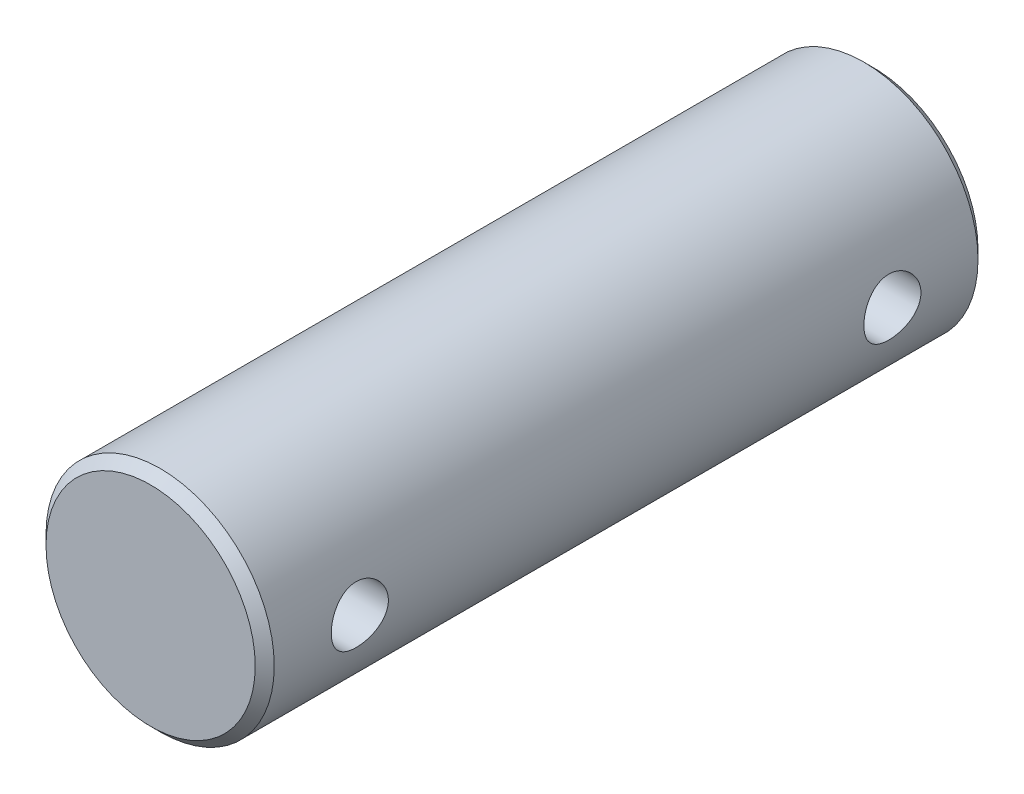
SolidWorks part; units mm, degrees
ref_plane "Front Plane" through (0, 0, 0) normal (0, 0, 1) x (1, 0, 0)
ref_plane "Top Plane" through (0, 0, 0) normal (0, 1, 0) x (1, 0, 0)
ref_plane "Right Plane" through (0, 0, 0) normal (1, 0, 0) x (0, 0, -1)
sketch "Sketch1" plane through (0, 0, 0) normal (0, 0, 1) x (1, 0, 0)
  circle A0 centre (0, 0) radius 6
  dimension "D1" = 12
extrude "Boss-Extrude1" add sketch "Sketch1" against normal blind 38
sketch "Sketch2" plane through (0, 0, 0) normal (1, 0, 0) x (0, 0, -1)
  line L0 (38, -6) -> (38, 6) construction
  circle A0 centre (5, 0) radius 1.5
  circle A1 centre (33, 0) radius 1.5
  dimension "D1" = 3
  dimension "D2" = 5
  dimension "D3" = 5
extrude "Cut-Extrude1" cut sketch "Sketch2" against normal through all both and the other way through all
chamfer "Chamfer1" distance 0.5 angle 45 2 edges at (6, 0, -38) (6, 0, 0)
